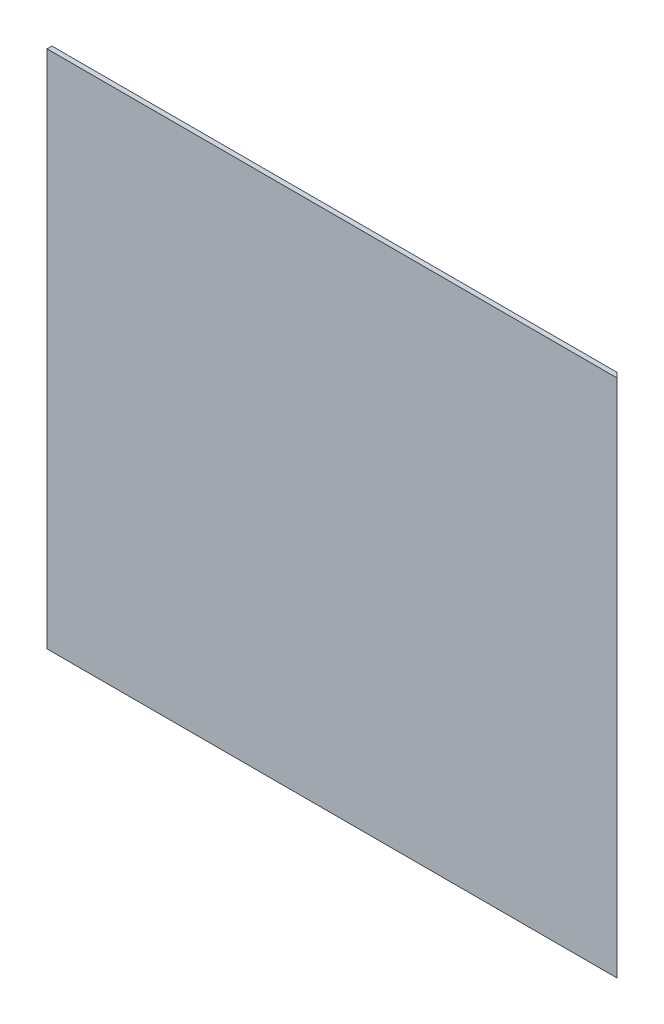
SolidWorks part; units mm, degrees
ref_plane "前视基准面" through (0, 0, 0) normal (0, 0, 1) x (1, 0, 0)
ref_plane "上视基准面" through (0, 0, 0) normal (0, 1, 0) x (1, 0, 0)
ref_plane "右视基准面" through (0, 0, 0) normal (1, 0, 0) x (0, 0, -1)
sketch "草图1" plane through (0, 0, 0) normal (0, 0, 1) x (1, 0, 0)
  line L1 (-175.5, 160) -> (175.5, 160)
  line L2 (-175.5, 160) -> (-175.5, -160)
  line L3 (-175.5, -160) -> (175.5, -160)
  line L4 (175.5, 160) -> (175.5, -160)
  line L5 (-175.5, 160) -> (175.5, -160) construction
  line L6 (-175.5, -160) -> (175.5, 160) construction
  point P0 (0, 0)
extrude "凸台-拉伸1" add sketch "草图1" along normal blind 3
sketch "草图2" plane through (0, 160, 0) normal (0, 1, 0) x (1, 0, 0)
  line L0 (175.5, -3) -> (172.5, 0)
  line L1 (175.5, 0) -> (-175.5, 0) construction
  line L2 (172.5, 0) -> (175.5, 0)
  line L3 (175.5, 0) -> (175.5, -3)
extrude "切除-拉伸1" cut sketch "草图2" against normal through all
